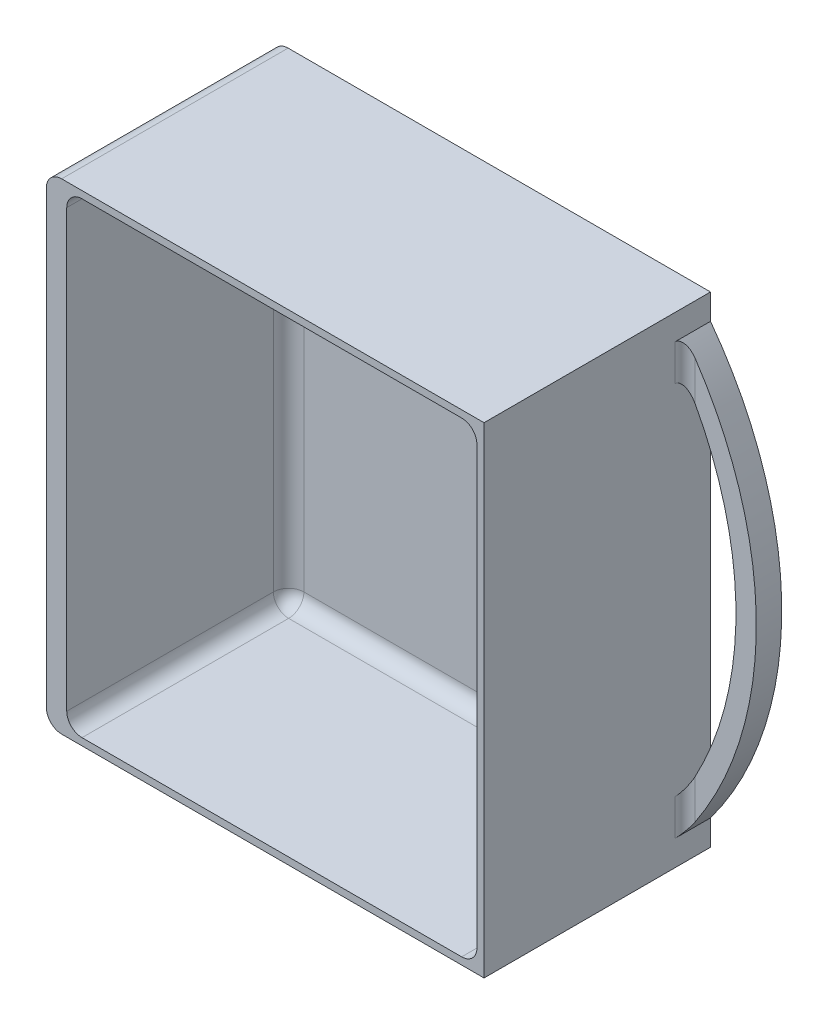
SolidWorks part; units mm, degrees
ref_plane "Спереди" through (0, 0, 0) normal (0, 0, 1) x (1, 0, 0)
ref_plane "Сверху" through (0, 0, 0) normal (0, 1, 0) x (1, 0, 0)
ref_plane "Справа" through (0, 0, 0) normal (1, 0, 0) x (0, 0, -1)
ref_plane "Плоскость4" through (0, 0, 22.25) normal (0, 0, 1) x (1, 0, 0)
sketch "Эскиз1" plane through (0, 0, 22.25) normal (0, 0, 1) x (1, 0, 0)
  line L0 (90, -47.25) -> (90, 47.25)
  line L1 (90, 47.25) -> (4, 47.25)
  line L2 (4, 47.25) -> (4, -47.25)
  line L3 (4, -47.25) -> (90, -47.25)
extrude "Бобышка-Вытянуть1" add sketch "Эскиз1" against normal blind 39.5
sketch "Эскиз2" plane through (0, 0, -17.25) normal (0, 0, -1) x (-1, 0, 0)
  line L0 (-90, -47.25) -> (-90, -42.25)
  line L1 (-90, 42.25) -> (-90, 47.25)
  line L2 (-90, 47.25) -> (-4, 47.25)
  line L3 (-4, 47.25) -> (-4, -47.25)
  line L4 (-4, -47.25) -> (-90, -47.25)
  line L5 (-90, -35.1432) -> (-90, 35.1432)
  arc A0 (-90, -42.25) -> (-90, 42.25) centre (-33.2478, 0) cw
  arc A1 (-90, 35.1432) -> (-90, -35.1432) centre (-33.2478, 0) ccw
extrude "Бобышка-Вытянуть2" add sketch "Эскиз2" along normal blind 5
sketch "Эскиз3" plane through (0, 0, 22.25) normal (0, 0, 1) x (1, 0, 0)
  line L0 (88.6, -45.85) -> (88.6, 45.85)
  line L1 (88.6, 45.85) -> (8, 45.85)
  line L2 (8, 45.85) -> (8, -45.85)
  line L3 (8, -45.85) -> (88.6, -45.85)
extrude "Вырез-Вытянуть1" cut sketch "Эскиз3" against normal blind 43.6
hole_wizard "Диаметр отверстия Ø8.3 (8.3)1" positions "Эскиз5" profile "Эскиз4" hole size "Ø8.3" standard "Ansi Metric"
sketch "Эскиз5" plane through (4, 0, 0) normal (-1, 0, 0) x (0, 0, 1)
  point P0 (0, 0)
sketch "Эскиз4" plane through (4, 0, 0) normal (0, 1, 0) x (0, 0, 1)
  line L0 (0, 0) -> (0, 3.2)
  line L1 (0, 3.2) -> (4.15, 3.2)
  line L2 (4.15, 3.2) -> (4.15, 0)
  line L5 (4.15, 0) -> (0, 0)
  line L10 (0, 3.2) -> (-4.15, 3.2) construction
  line L11 (0, -6.35) -> (0, 107.95) construction
  dimension "Диаметр отверстия" = 8.3
  dimension "Глубина отверстия" = 3.2
  dimension "Угол заточки сверла" = 180
fillet "Скругление1" radius 3 2 edges at (4, -47.25, 0) (4, 47.25, 0)
sketch "Эскиз7" plane through (4, 0, 0) normal (-1, 0, 0) x (0, 0, 1)
  circle A0 centre (0, 0) radius 4.2
  dimension "D1" = 8.4
extrude "Бобышка-Вытянуть3" add sketch "Эскиз7" against normal blind 3.8
fillet "Скругление2" radius 3 1 edges at (8, 0, -21.35)
fillet "Скругление3" radius 3 3 edges at (8, -45.85, 1.95) (49.8, -45.85, -21.35) (8.8787, -45.85, -20.4713)
fillet "Скругление4" radius 3 3 edges at (49.8, 45.85, -21.35) (8, 45.85, 1.95) (8.8787, 45.85, -20.4713)
fillet "Скругление5" radius 3 5 edges at (88.6, -45.85, 1.95) (88.6, 0, -21.35) (88.6, -44.9713, -20.4713) (88.6, 45.85, 1.95) (88.6, 44.9713, -20.4713)
fillet "Скругление6" radius 2 2 edges at (90, -38.6966, -17.25) (90, 38.6966, -17.25)
